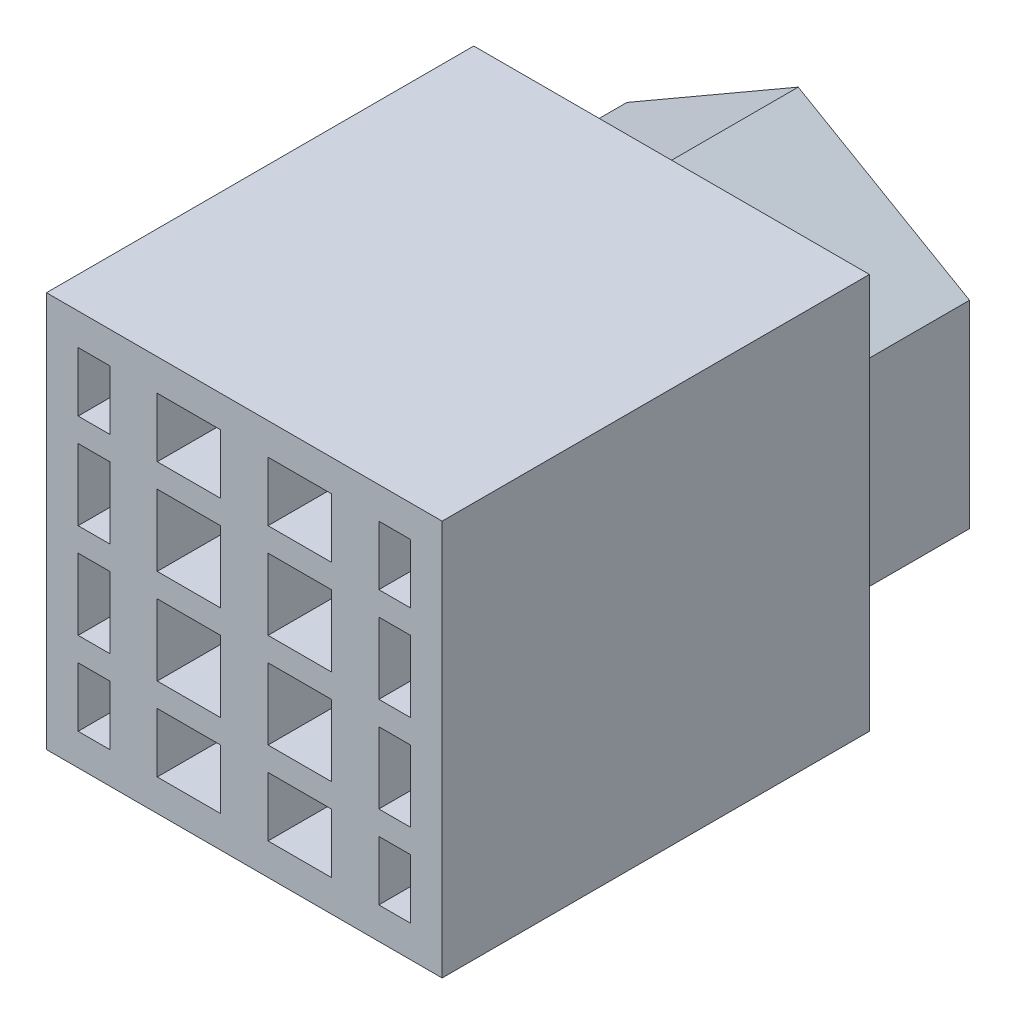
SolidWorks part; units mm, degrees
ref_plane "前视基准面" through (0, 0, 0) normal (0, 0, 1) x (1, 0, 0)
ref_plane "上视基准面" through (0, 0, 0) normal (0, 1, 0) x (1, 0, 0)
ref_plane "右视基准面" through (0, 0, 0) normal (1, 0, 0) x (0, 0, -1)
sketch "草图8" plane through (0, 0, 0) normal (0, 0, 1) x (1, 0, 0)
  line L0 (0, 7.8741) -> (0, -9.2542) construction
  line L1 (-12.5, -12.5) -> (12.5, -12.5)
  line L2 (-12.5, -12.5) -> (-12.5, 12.5)
  line L3 (-12.5, 12.5) -> (12.5, 12.5)
  line L4 (12.5, -12.5) -> (12.5, 12.5)
  line L5 (-12.5, -12.5) -> (12.5, 12.5) construction
  line L6 (-12.5, 12.5) -> (12.5, -12.5) construction
  line L7 (-16.0619, 0) -> (15.5648, 0) construction
  line L8 (-3.5, 7.8741) -> (-3.5, -9.2542) construction
  line L9 (-9.5, 7.8741) -> (-9.5, -9.2542) construction
  line L10 (5.5, 10.5) -> (1.5, 10.5)
  line L15 (-5.5, -10.5) -> (-1.5, -10.5)
  line L20 (-5.5, -10.5) -> (-5.5, 10.5)
  line L21 (-5.5, 10.5) -> (-1.5, 10.5)
  line L26 (-1.5, -10.5) -> (-1.5, 10.5)
  line L27 (-5.5, -10.5) -> (-1.5, 10.5) construction
  line L28 (-5.5, 10.5) -> (-1.5, -10.5) construction
  line L29 (-10.5, -10.5) -> (-8.5, -10.5)
  line L30 (-10.5, -10.5) -> (-10.5, 10.5)
  line L31 (-10.5, 10.5) -> (-8.5, 10.5)
  line L32 (-8.5, -10.5) -> (-8.5, 10.5)
  line L33 (-10.5, -10.5) -> (-8.5, 10.5) construction
  line L34 (-10.5, 10.5) -> (-8.5, -10.5) construction
  line L35 (1.5, -10.5) -> (1.5, 10.5)
  line L36 (5.5, -10.5) -> (1.5, -10.5)
  line L37 (5.5, -10.5) -> (5.5, 10.5)
  line L38 (10.5, 10.5) -> (8.5, 10.5)
  line L39 (8.5, -10.5) -> (8.5, 10.5)
  line L40 (10.5, -10.5) -> (8.5, -10.5)
  line L41 (10.5, -10.5) -> (10.5, 10.5)
  point P0 (0, 0)
  point P14 (-7, 0)
  point P15 (-3.5, 0)
  point P17 (-3, 0)
  point P21 (-9.5, 0)
  point P22 (-9, 0)
  dimension "D1" = 3.5
  dimension "D2" = 6
extrude "凸台-拉伸7" add sketch "草图8" along normal blind 25
sketch "草图9" plane through (0, 0, 0) normal (0, 0, -1) x (-1, 0, 0)
  line L1 (-12.5, -12.5) -> (12.5, -12.5)
  line L2 (-12.5, -12.5) -> (-12.5, 12.5)
  line L3 (-12.5, 12.5) -> (12.5, 12.5)
  line L4 (12.5, -12.5) -> (12.5, 12.5)
  line L5 (-12.5, -12.5) -> (12.5, 12.5) construction
  line L6 (-12.5, 12.5) -> (12.5, -12.5) construction
  point P0 (0, 0)
extrude "凸台-拉伸8" add sketch "草图9" along normal blind 2
sketch "草图14" plane through (0, 0, 25) normal (0, 0, 1) x (1, 0, 0)
  line L0 (-16.6961, 0) -> (20.7273, 0) construction
  line L1 (-12.5, 12.5) -> (-12.5, -12.5) construction
  line L2 (12.5, -0.75) -> (-12.5, -0.75)
  line L3 (12.5, -0.75) -> (12.5, 0.75)
  line L4 (12.5, 0.75) -> (-12.5, 0.75)
  line L5 (-12.5, -0.75) -> (-12.5, 0.75)
  line L6 (12.5, -0.75) -> (-12.5, 0.75) construction
  line L7 (12.5, 0.75) -> (-12.5, -0.75) construction
  line L12 (12.5, 5.25) -> (-12.5, 5.25)
  line L13 (12.5, 5.25) -> (12.5, 6.75)
  line L14 (12.5, 6.75) -> (-12.5, 6.75)
  line L15 (-12.5, 5.25) -> (-12.5, 6.75)
  line L16 (12.5, 5.25) -> (-12.5, 6.75) construction
  line L17 (12.5, 6.75) -> (-12.5, 5.25) construction
  line L18 (12.5, -6.75) -> (-12.5, -5.25) construction
  line L19 (12.5, -5.25) -> (-12.5, -6.75) construction
  line L20 (-12.5, -5.25) -> (-12.5, -6.75)
  line L21 (12.5, -6.75) -> (-12.5, -6.75)
  line L22 (12.5, -5.25) -> (12.5, -6.75)
  line L23 (12.5, -5.25) -> (-12.5, -5.25)
  point P3 (0, 0)
  point P11 (0, 6)
  point P19 (0, -6)
  dimension "D1" = 2
extrude "凸台-拉伸11" add sketch "草图14" against normal blind 25
sketch "草图16" plane through (0, 0, -2) normal (0, 0, -1) x (-1, 0, 0)
  line L0 (0, -10.1906) -> (8.8253, -5.0953)
  line L1 (0, -12.5) -> (10.8253, -6.25)
  line L2 (10.8253, -6.25) -> (10.8253, 6.25)
  line L3 (10.8253, 6.25) -> (0, 12.5)
  line L4 (0, 12.5) -> (-10.8253, 6.25)
  line L5 (-10.8253, 6.25) -> (-10.8253, -6.25)
  line L6 (-10.8253, -6.25) -> (0, -12.5)
  line L7 (8.8253, -5.0953) -> (8.8253, 5.0953)
  line L8 (8.8253, 5.0953) -> (0, 10.1906)
  line L9 (0, 10.1906) -> (-8.8253, 5.0953)
  line L10 (-8.8253, 5.0953) -> (-8.8253, -5.0953)
  line L11 (-8.8253, -5.0953) -> (0, -10.1906)
  circle A0 centre (0, 0) radius 12.5 construction
  dimension "D1" = 2
extrude "凸台-拉伸14" add sketch "草图16" along normal blind 6
sketch "草图18" plane through (0, 0, -8) normal (0, 0, -1) x (-1, 0, 0)
  line L1 (0, 12.5) -> (-10.8253, 6.25)
  line L2 (-10.8253, 6.25) -> (-10.8253, -6.25)
  line L3 (-10.8253, -6.25) -> (0, -12.5)
  line L4 (0, -12.5) -> (10.8253, -6.25)
  line L5 (10.8253, -6.25) -> (10.8253, 6.25)
  line L6 (10.8253, 6.25) -> (0, 12.5)
  circle A0 centre (0, 0) radius 10.8253 construction
extrude "凸台-拉伸16" add sketch "草图18" along normal blind 2
sketch "草图19" plane through (0, 12.5, 0) normal (0, 1, 0) x (1, 0, 0)
  line L0 (7.0547, -25) -> (7.0547, 2)
  line L1 (12.5, -25) -> (-12.5, -25) construction
  line L2 (0, 2) -> (12.5, 2) construction
  line L3 (-12.5, -20) -> (12.5, -20)
  line L4 (-12.5, -25) -> (-12.5, 2) construction
  line L5 (12.5, -25) -> (12.5, 2) construction
  dimension "D1" = 5
sketch "草图20" plane through (0, -12.5, 0) normal (0, -1, 0) x (1, 0, 0)
  line L0 (7.0547, 25) -> (7.0547, -2)
  line L1 (-12.5, 20) -> (12.5, 20)
